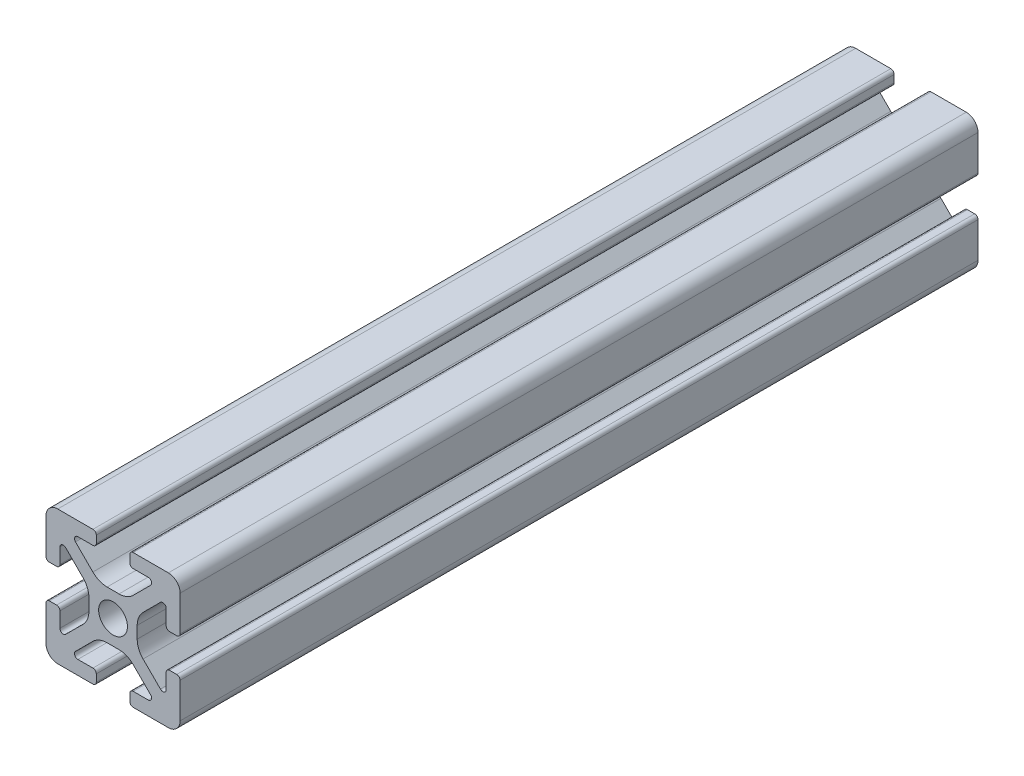
SolidWorks part; units mm, degrees
material "1060 Alloy"
ref_plane "Front Plane" through (0, 0, 0) normal (0, 0, 1) x (1, 0, 0)
ref_plane "Top Plane" through (0, 0, 0) normal (0, 1, 0) x (1, 0, 0)
ref_plane "Right Plane" through (0, 0, 0) normal (1, 0, 0) x (0, 0, -1)
sketch "Sketch2" plane through (0, 0, 0) normal (0, 0, 1) x (1, 0, 0)
  line L0 (0, 10) -> (0, -10) construction
  line L1 (-10, 0) -> (10, 0) construction
  line L2 (2.5, -10) -> (10, -10)
  line L3 (10, -10) -> (10, -2.5)
  line L4 (2.5, -10) -> (2.5, -7.9246)
  line L5 (2.5, -7.9246) -> (6.4571, -7.9246)
  line L6 (6.4571, -7.9246) -> (2.1325, -3.6)
  line L7 (0, 0) -> (10, -10) construction
  line L8 (10, -2.5) -> (7.9246, -2.5)
  line L9 (7.9246, -2.5) -> (7.9246, -6.4571)
  line L10 (7.9246, -6.4571) -> (3.6, -2.1325)
  line L11 (5.7623, -4.2948) -> (4.2948, -5.7623) construction
  circle A0 centre (0, 0) radius 2.15
  arc A1 (5.25, -7.9246) -> (5.6036, -7.0711) centre (5.25, -7.4246) ccw construction
  point P8 (0, -3.6)
  point P16 (5.0286, -5.0286)
  dimension "Center Hole Diameter" = 4.3
  dimension "D3" = 0.5
  dimension "Rail Height" = 20
  dimension "Rail Width" = 20
  dimension "T-Slot Width" = 5
  dimension "Slot Depth" = 6.4
  dimension "Slot Inner Width" = 11.5
sketch "Sketch3" plane through (0, 0, 0) normal (1, 0, 0) x (0, 0, -1)
  line L0 (-609.6, -10) -> (609.6, -10) construction
  line L1 (-584.2, 0) -> (584.2, 0) construction
  line L2 (0, 10) -> (0, -10) construction
  line L3 (0, 10) -> (0, -10) construction
  point P6 (-584.2, 0)
  point P8 (584.2, 0)
  dimension "D1" = 25.4
  dimension "Length" = 1219.2
sketch "Sketch4" plane through (0, 0, 0) normal (0, 0, 1) x (1, 0, 0)
  line L0 (3, -10) -> (8.25, -10)
  line L1 (2.5, -10) -> (10, -10) construction
  line L2 (2.5, -10) -> (2.5, -7.9246) construction
  line L3 (2.5, -7.9246) -> (6.4571, -7.9246) construction
  line L4 (2.5, -8.4246) -> (2.5, -9.5)
  line L5 (3, -7.9246) -> (5.25, -7.9246)
  line L6 (0, -3.6) -> (0.8898, -3.6)
  line L7 (6.4571, -7.9246) -> (2.1325, -3.6) construction
  line L8 (3.0112, -4.4787) -> (5.6036, -7.0711)
  line L9 (10, -10) -> (10, -2.5) construction
  line L10 (7.9246, -6.4571) -> (3.6, -2.1325) construction
  line L11 (7.9246, -2.5) -> (7.9246, -6.4571) construction
  line L12 (7.9246, -5.25) -> (7.9246, -3)
  line L13 (10, -2.5) -> (7.9246, -2.5) construction
  line L14 (8.4246, -2.5) -> (9.5, -2.5)
  line L15 (10, -3) -> (10, -8.25)
  line L16 (7.0711, -5.6036) -> (4.4787, -3.0112)
  line L17 (3.6, 0) -> (3.6, -0.8898)
  line L18 (-10, 0) -> (10, 0) construction
  line L19 (0, -3.6) -> (0, -2.15)
  line L20 (0, 10) -> (0, -10) construction
  line L21 (3.6, 0) -> (2.15, 0)
  arc A0 (2.5, -9.5) -> (3, -10) centre (3, -9.5) ccw
  arc A1 (5.25, -7.9246) -> (5.6036, -7.0711) centre (5.25, -7.4246) ccw construction
  arc A2 (2.5, -8.4246) -> (3, -7.9246) centre (3, -8.4246) cw
  arc A3 (5.25, -7.9246) -> (5.6036, -7.0711) centre (5.25, -7.4246) ccw
  arc A4 (0.8898, -3.6) -> (3.0112, -4.4787) centre (0.8898, -6.6) cw
  arc A5 (8.25, -10) -> (10, -8.25) centre (8.25, -8.25) ccw
  arc A6 (7.0711, -5.6036) -> (7.9246, -5.25) centre (7.4246, -5.25) ccw
  arc A7 (7.9246, -3) -> (8.4246, -2.5) centre (8.4246, -3) cw
  arc A8 (9.5, -2.5) -> (10, -3) centre (9.5, -3) cw
  arc A9 (4.4787, -3.0112) -> (3.6, -0.8898) centre (6.6, -0.8898) cw
  circle A10 centre (0, 0) radius 2.15 construction
  arc A11 (0, -2.15) -> (2.15, 0) centre (0, 0) ccw
  dimension "D1" = 1.75
  dimension "D2" = 3
extrude "Boss-Extrude1" add sketch "Sketch4" along normal mid plane 119.01
mirror "Mirror1" about plane through (0, 0, 0) normal (1, 0, 0) of bodies 134
mirror "Mirror2" about plane through (0, 0, 0) normal (0, 1, 0) of bodies 135
equation "\"D3@Sketch2\"=\"T-Slot Width@Sketch2\"*0.1"
equation "\"D1@Sketch4\"=\"D3@Sketch2\"*3.5"
equation "\"D2@Sketch4\"=\"D3@Sketch2\"*6"
